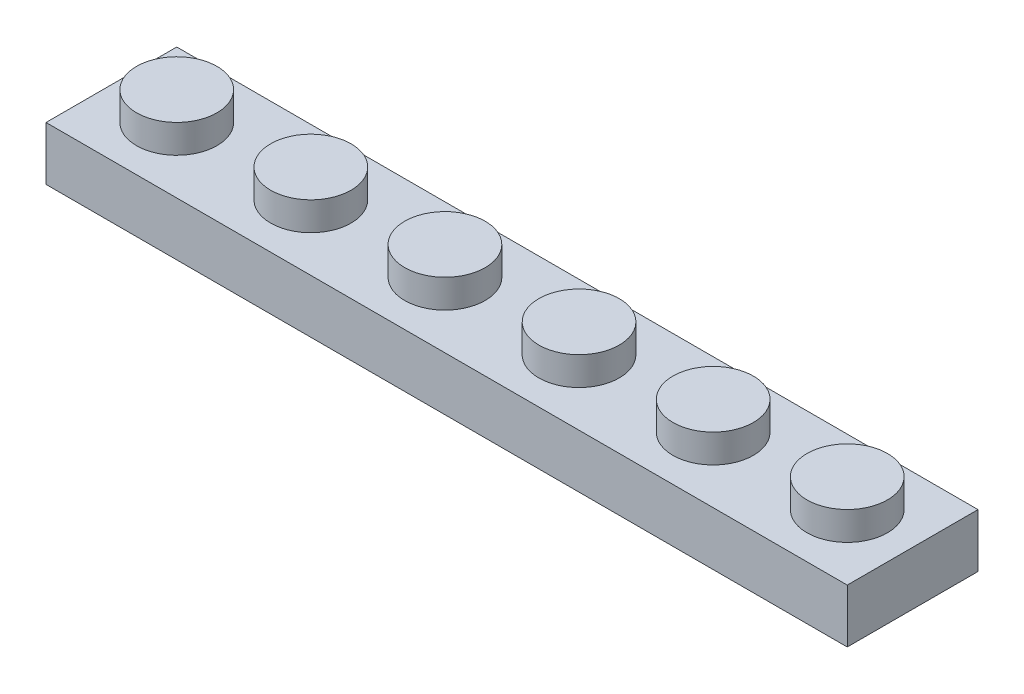
SolidWorks part; units mm, degrees
ref_plane "Спереди" through (0, 0, 0) normal (0, 0, 1) x (1, 0, 0)
ref_plane "Сверху" through (0, 0, 0) normal (0, 1, 0) x (1, 0, 0)
ref_plane "Справа" through (0, 0, 0) normal (1, 0, 0) x (0, 0, -1)
sketch "Эскиз1" plane through (0, 0, 0) normal (0, 1, 0) x (1, 0, 0)
  line L1 (23.9, -3.9) -> (-23.9, -3.9)
  line L2 (23.9, -3.9) -> (23.9, 3.9)
  line L3 (23.9, 3.9) -> (-23.9, 3.9)
  line L4 (-23.9, -3.9) -> (-23.9, 3.9)
  line L5 (23.9, -3.9) -> (-23.9, 3.9) construction
  line L6 (23.9, 3.9) -> (-23.9, -3.9) construction
  point P0 (0, 0)
  dimension "D1" = 47.8
  dimension "D2" = 7.8
extrude "Бобышка-Вытянуть1" add sketch "Эскиз1" along normal blind 3.2
sketch "Эскиз2" plane through (0, 3.2, 0) normal (0, 1, 0) x (1, 0, 0)
  line L0 (-23.9, 3.9) -> (-23.9, -3.9) construction
  line L1 (23.9, 3.9) -> (-23.9, 3.9) construction
  circle A0 centre (-20, 0) radius 2.4
  circle A1 centre (-12, 0) radius 2.4
  circle A2 centre (-4, 0) radius 2.4
  circle A3 centre (4, 0) radius 2.4
  circle A4 centre (12, 0) radius 2.4
  circle A5 centre (20, 0) radius 2.4
  dimension "D1" = 3.9
  dimension "D2" = 3.9
  dimension "D4" = 8
  dimension "D3" = 6
extrude "Бобышка-Вытянуть2" add sketch "Эскиз2" along normal blind 1.7
sketch "Эскиз3" plane through (0, 0, 0) normal (0, -1, 0) x (1, 0, 0)
  line L0 (-23.9, -3.9) -> (-23.9, 3.9) construction
  circle A0 centre (-20, 0) radius 2.5
  circle A1 centre (-12, 0) radius 2.5
  circle A2 centre (-4, 0) radius 2.5
  circle A3 centre (4, 0) radius 2.5
  circle A4 centre (12, 0) radius 2.5
  circle A5 centre (20, 0) radius 2.5
  dimension "D1" = 3.9
  dimension "D3" = 8
  dimension "D2" = 6
extrude "Вырез-Вытянуть1" cut sketch "Эскиз3" against normal blind 1.8
